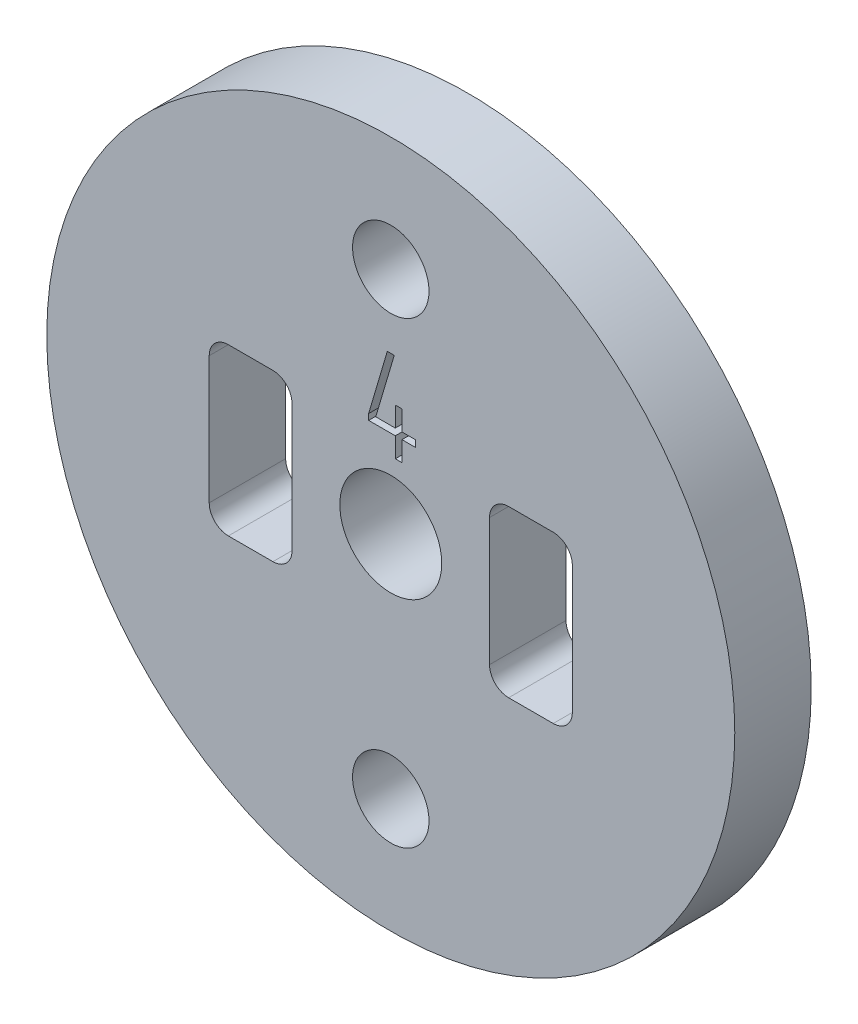
SolidWorks part; units mm, degrees
ref_plane "Alzado" through (0, 0, 0) normal (0, 0, 1) x (1, 0, 0)
ref_plane "Planta" through (0, 0, 0) normal (0, 1, 0) x (1, 0, 0)
ref_plane "Vista lateral" through (0, 0, 0) normal (1, 0, 0) x (0, 0, -1)
sketch "Model" plane through (0, 0, 0) normal (0, 0, 1) x (1, 0, 0)
  line L0 (27.5429, 289.3924) -> (25.7929, 289.3924)
  line L1 (28.2929, 283.6424) -> (28.2929, 288.6424)
  line L2 (25.7929, 282.8924) -> (27.5429, 282.8924)
  line L3 (25.0429, 288.6424) -> (25.0429, 283.6424)
  line L4 (14.7929, 289.3924) -> (16.5429, 289.3924)
  line L5 (14.0429, 283.6424) -> (14.0429, 288.6424)
  line L6 (16.5429, 282.8924) -> (14.7929, 282.8924)
  line L7 (17.2929, 288.6424) -> (17.2929, 283.6424)
  circle A0 centre (21.1679, 286.1424) radius 2
  arc A1 (25.7929, 289.3924) -> (25.0429, 288.6424) centre (25.7929, 288.6424) ccw
  arc A2 (28.2929, 288.6424) -> (27.5429, 289.3924) centre (27.5429, 288.6424) ccw
  arc A3 (27.5429, 282.8924) -> (28.2929, 283.6424) centre (27.5429, 283.6424) ccw
  arc A4 (25.0429, 283.6424) -> (25.7929, 282.8924) centre (25.7929, 283.6424) ccw
  arc A5 (17.2929, 288.6424) -> (16.5429, 289.3924) centre (16.5429, 288.6424) ccw
  arc A6 (14.7929, 289.3924) -> (14.0429, 288.6424) centre (14.7929, 288.6424) ccw
  arc A7 (14.0429, 283.6424) -> (14.7929, 282.8924) centre (14.7929, 283.6424) ccw
  arc A8 (16.5429, 282.8924) -> (17.2929, 283.6424) centre (16.5429, 283.6424) ccw
  circle A9 centre (21.1679, 295.1424) radius 1.5
  circle A10 centre (21.1679, 277.1424) radius 1.5
  circle A11 centre (21.1679, 286.1424) radius 13.5
  text T0 "4" font "SOLID EDGE ISO" height 3.5
extrude "Saliente-Extruir1" add sketch "Model" along normal blind 3
